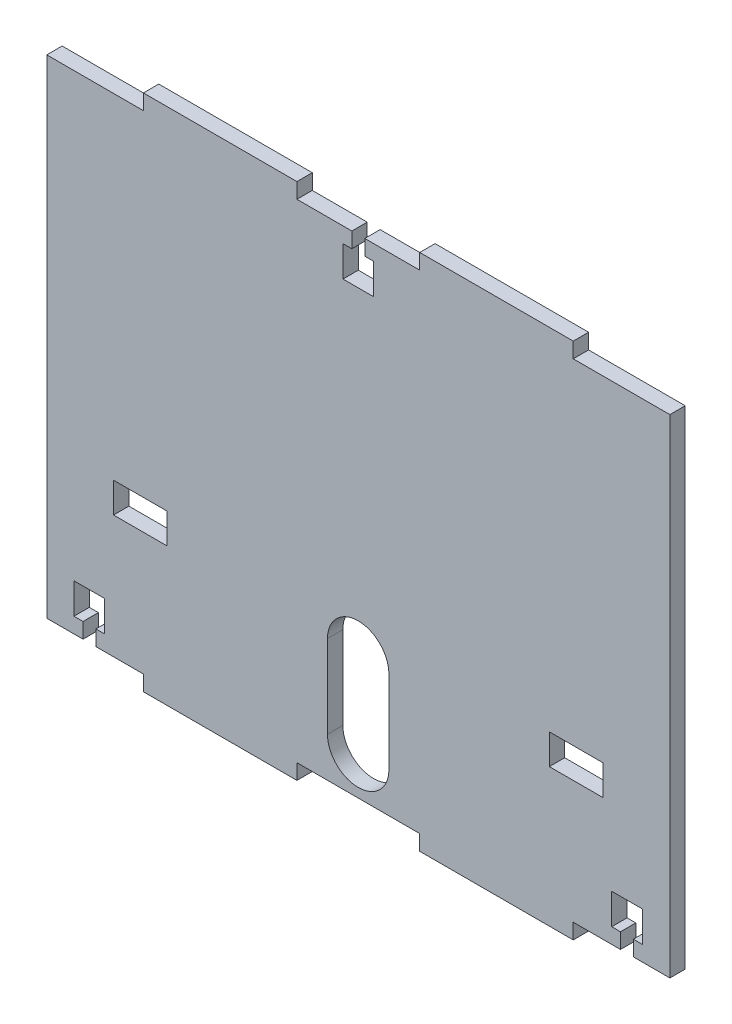
SolidWorks part; units mm, degrees
ref_plane "Plan de face" through (0, 0, 0) normal (0, 0, 1) x (1, 0, 0)
ref_plane "Plan de dessus" through (0, 0, 0) normal (0, 1, 0) x (1, 0, 0)
ref_plane "Plan de droite" through (0, 0, 0) normal (1, 0, 0) x (0, 0, -1)
sketch "Esquisse1" plane through (0, 0, 0) normal (0, 0, 1) x (1, 0, 0)
  line L0 (-179.3574, 206.2715) -> (-179.3574, 47.3515)
  line L1 (-179.3574, 47.3515) -> (-167.5515, 47.3515)
  line L2 (-147.8874, 47.3515) -> (-147.8874, 42.3515)
  line L3 (-147.8874, 42.3515) -> (-97.8874, 42.3515)
  line L4 (-97.8874, 42.3515) -> (-97.8874, 47.3515)
  line L5 (-97.8874, 47.3515) -> (-79.9874, 47.3515)
  line L6 (-179.3574, 126.8115) -> (-77.9294, 126.8115) construction
  line L7 (-73.6674, 47.3515) -> (-79.9874, 47.3515)
  line L9 (-57.8874, 42.3515) -> (-57.8874, 47.3515)
  line L11 (23.5826, 47.3515) -> (18.0126, 47.3515)
  line L12 (23.5826, 206.2715) -> (23.5826, 47.3515)
  line L13 (23.5826, 206.2715) -> (-7.8874, 206.2715)
  line L15 (-57.8874, 211.2715) -> (-57.8874, 206.2715)
  line L17 (-97.8874, 206.2715) -> (-79.9874, 206.2715)
  line L18 (-97.8874, 211.2715) -> (-97.8874, 206.2715)
  line L19 (-147.8874, 211.2715) -> (-97.8874, 211.2715)
  line L20 (-147.8874, 206.2715) -> (-147.8874, 211.2715)
  line L21 (-179.3574, 206.2715) -> (-147.8874, 206.2715)
  line L33 (-73.6674, 47.3515) -> (-57.8874, 47.3515)
  line L34 (-79.9874, 206.2715) -> (-79.9874, 201.2715)
  line L45 (-73.6674, 206.2715) -> (-57.8874, 206.2715)
  line L46 (-75.7874, 201.2715) -> (-75.7874, 206.2715)
  line L47 (-30.9874, 42.3515) -> (-30.9874, 73.3277) construction
  line L70 (-161.5174, 47.3515) -> (-147.8874, 47.3515)
  line L72 (-77.9294, 25.0099) -> (-77.9294, 104.2609) construction
  line L73 (-77.9294, 60.3515) -> (-77.9294, 87.3515) construction
  line L74 (-87.9294, 60.3515) -> (-87.9294, 87.3515)
  line L75 (-67.9294, 60.3515) -> (-67.9294, 87.3515)
  line L76 (11.6927, 47.3515) -> (18.0126, 47.3515)
  line L77 (7.4927, 47.3515) -> (7.4927, 52.3515)
  line L87 (11.6927, 52.3515) -> (11.6927, 47.3515)
  line L91 (-163.3515, 47.3515) -> (-163.3515, 52.3515)
  line L92 (-167.5515, 52.3515) -> (-167.5515, 47.3515)
  line L99 (-161.5174, 47.3515) -> (-163.3515, 47.3515)
  line L100 (-75.7874, 206.2715) -> (-73.6674, 206.2715)
  line L101 (-79.9874, 201.2715) -> (-82.8874, 201.2715)
  line L102 (-82.8874, 201.2715) -> (-82.8874, 191.2715)
  line L103 (-82.8874, 191.2715) -> (-72.8874, 191.2715)
  line L104 (-72.8874, 191.2715) -> (-72.8874, 201.2715)
  line L105 (-72.8874, 201.2715) -> (-75.7874, 201.2715)
  line L106 (-163.3515, 52.3515) -> (-160.5115, 52.3515)
  line L107 (-160.5115, 52.3515) -> (-160.5115, 62.3515)
  line L108 (-160.5115, 62.3515) -> (-170.5115, 62.3515)
  line L109 (-170.5115, 62.3515) -> (-170.5115, 52.3515)
  line L110 (-170.5115, 52.3515) -> (-167.5515, 52.3515)
  line L111 (7.4927, 52.3515) -> (4.6527, 52.3515)
  line L112 (4.6527, 52.3515) -> (4.6527, 62.3515)
  line L113 (14.6527, 52.3515) -> (11.6927, 52.3515)
  line L114 (14.6527, 62.3515) -> (14.6527, 52.3515)
  line L115 (4.6527, 62.3515) -> (14.6527, 62.3515)
  line L116 (-57.8874, 211.2715) -> (-7.8874, 211.2715)
  line L117 (-7.8874, 211.2715) -> (-7.8874, 206.2715)
  line L118 (-57.8874, 42.3515) -> (-7.8874, 42.3515)
  line L119 (-7.8874, 42.3515) -> (-7.8874, 47.3515)
  line L120 (-7.8874, 47.3515) -> (7.4927, 47.3515)
  line L121 (-15.6687, 97.168) -> (-15.6687, 87.3515)
  line L122 (-157.6167, 97.168) -> (-140.1901, 97.168)
  line L123 (-157.6167, 97.168) -> (-157.6167, 87.3515)
  line L124 (-157.6167, 87.3515) -> (-140.1901, 87.3515)
  line L125 (-140.1901, 97.168) -> (-140.1901, 87.3515)
  line L126 (1.7579, 87.3515) -> (-15.6687, 87.3515)
  line L127 (1.7579, 97.168) -> (1.7579, 87.3515)
  line L128 (1.7579, 97.168) -> (-15.6687, 97.168)
  arc A0 (-87.9294, 60.3515) -> (-67.9294, 60.3515) centre (-77.9294, 60.3515) ccw
  arc A1 (-67.9294, 87.3515) -> (-87.9294, 87.3515) centre (-77.9294, 87.3515) ccw
  point P15 (23.5826, 126.8115)
  point P28 (-77.9294, 73.8515)
  dimension "D6" = 27
  dimension "D7" = 13
  dimension "D14" = 10
  dimension "D1" = 79.46
  dimension "D2" = 31.47
  dimension "D3" = 50
  dimension "D4" = 10
  dimension "D5" = 5
  dimension "D8" = 50
  dimension "D9" = 5
  dimension "D10" = 2.9
  dimension "D11" = 10
  dimension "D12" = 10
  dimension "D13" = 2.84
  dimension "D15" = 10
  dimension "D16" = 5
  dimension "D17" = 5
  dimension "D18" = 50
extrude "Boss.-Extru.2" add sketch "Esquisse1" along normal blind 5
